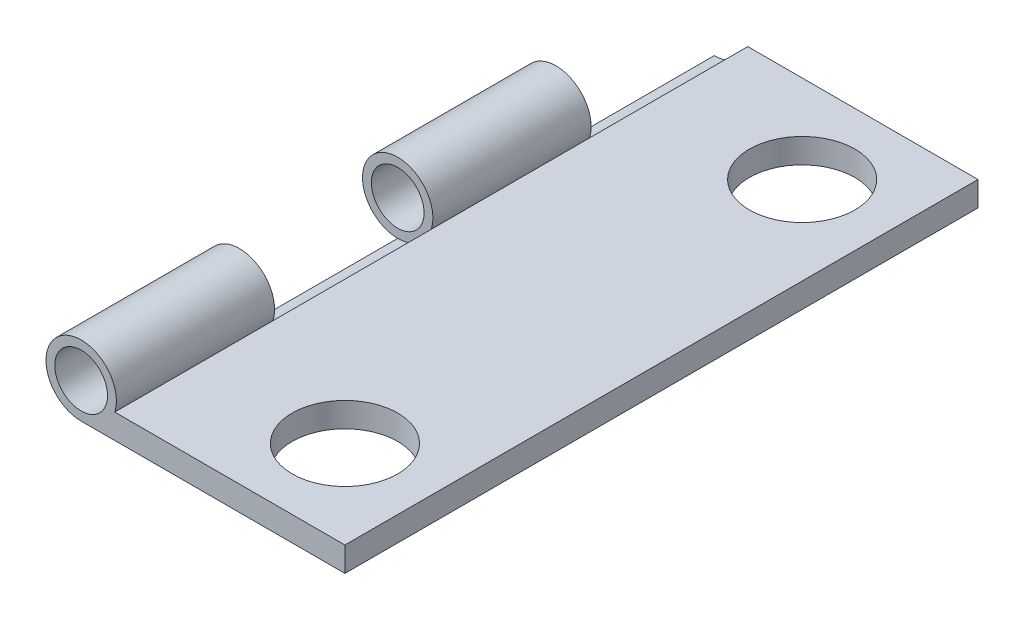
SolidWorks part; units mm, degrees
material "Aluminum Bronze"
ref_plane "Front" through (0, 0, 0) normal (0, 0, 1) x (1, 0, 0)
ref_plane "Top" through (0, 0, 0) normal (0, 1, 0) x (1, 0, 0)
ref_plane "Right" through (0, 0, 0) normal (1, 0, 0) x (0, 0, -1)
sketch "Sketch1" plane through (0, 0, 0) normal (0, 1, 0) x (1, 0, 0)
  line L1 (0, 0) -> (7.5, 0)
  line L2 (0, 0) -> (0, 18)
  line L3 (0, 18) -> (7.5, 18)
  line L4 (7.5, 0) -> (7.5, 18)
  dimension "D1" = 7.5
  dimension "D2" = 18
extrude "Boss-Extrude1" add sketch "Sketch1" along normal blind 0.7
sketch "Sketch2" plane through (0, 0, 0) normal (0, 0, 1) x (1, 0, 0)
  line L0 (0, 0) -> (7.5, 0) construction
  circle A0 centre (0, 1) radius 1
  dimension "D2" = 2
  dimension "D1" = 1
extrude "Boss-Extrude2" add sketch "Sketch2" against normal through all
sketch "Sketch4" plane through (0, 0, 0) normal (0, 0, 1) x (1, 0, 0)
  circle A0 centre (0, 1) radius 0.75
  dimension "D1" = 1.5
extrude "Cut-Extrude1" cut sketch "Sketch4" against normal through all
sketch "Sketch5" plane through (0, 0, 0) normal (0, 0, 1) x (1, 0, 0)
  circle A0 centre (0, 1) radius 1
extrude "Cut-Extrude2" cut sketch "Sketch5" against normal blind 4.5 from offset 4.5 offset against normal yes
pattern_linear "LPattern1" count 2 spacing 9 along (0, 0, -1) of "Cut-Extrude2"
sketch "Sketch6" plane through (0, 0.7, 0) normal (0, 1, 0) x (1, 0, 0)
  line L0 (0.9539, 0) -> (7.5, 0) construction
  line L1 (7.5, 0) -> (7.5, 18) construction
  line L2 (7.5, 9) -> (-1, 9) construction
  circle A0 centre (5, 2.5) radius 1.5
  circle A1 centre (5, 15.5) radius 1.5
  dimension "D1" = 3
  dimension "D2" = 2.5
  dimension "D3" = 2.5
extrude "Cut-Extrude3" cut sketch "Sketch6" against normal through all
